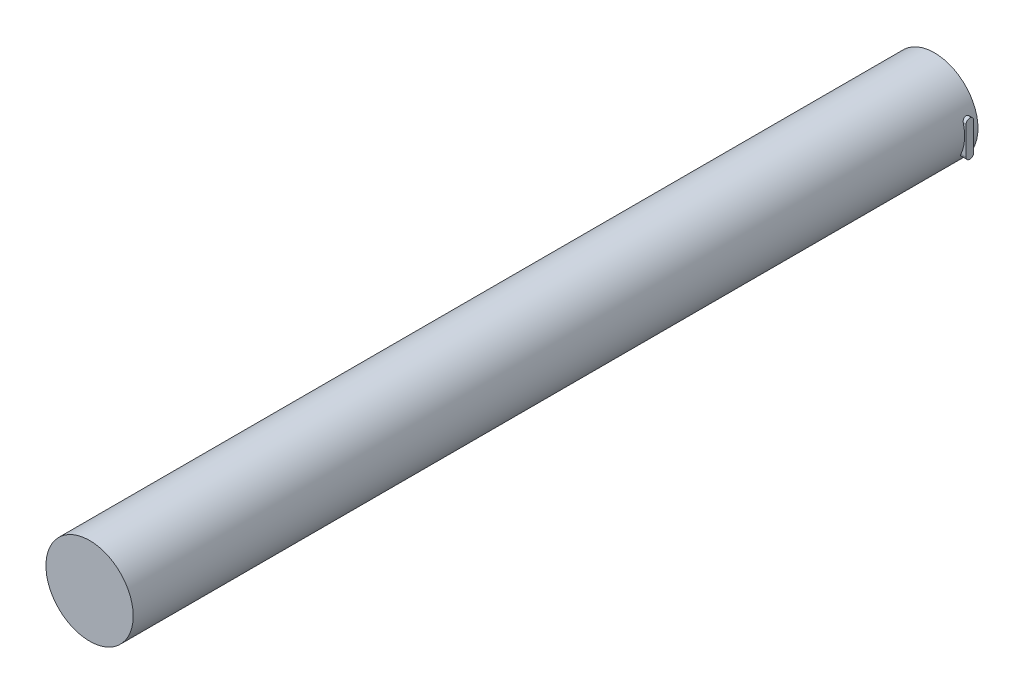
SolidWorks part; units mm, degrees
ref_plane "Front Plane" through (0, 0, 0) normal (0, 0, 1) x (1, 0, 0)
ref_plane "Top Plane" through (0, 0, 0) normal (0, 1, 0) x (1, 0, 0)
ref_plane "Right Plane" through (0, 0, 0) normal (1, 0, 0) x (0, 0, -1)
sketch "Sketch1" plane through (0, 0, 0) normal (0, 0, 1) x (1, 0, 0)
  circle A0 centre (0, 0) radius 9.8425
  dimension "D1" = 19.685
extrude "Boss-Extrude1" add sketch "Sketch1" along normal blind 190.5
sketch "Sketch2" plane through (0, 0, 190.5) normal (0, 0, 1) x (1, 0, 0)
  circle A0 centre (0, 0) radius 9.398
  dimension "D1" = 18.796
sketch "Sketch6" plane through (0, 0, 0) normal (1, 0, 0) x (0, 0, -1)
  line L0 (-2.1612, 2.396) -> (-2.1612, -3.954) construction
  line L1 (-1.3017, 2.396) -> (-1.3017, -3.954)
  line L2 (-3.0208, 2.396) -> (-3.0208, -3.954)
  arc A0 (-1.3017, 2.396) -> (-3.0208, 2.396) centre (-2.1612, 2.396) ccw
  arc A1 (-3.0208, -3.954) -> (-1.3017, -3.954) centre (-2.1612, -3.954) ccw
  point P2 (-2.1612, -0.779)
  dimension "D1" = 1.7191
  dimension "D2" = 6.35
extrude "Boss-Extrude6" add sketch "Sketch6" along normal blind 10.16 contours L1 A1 L2 A0
